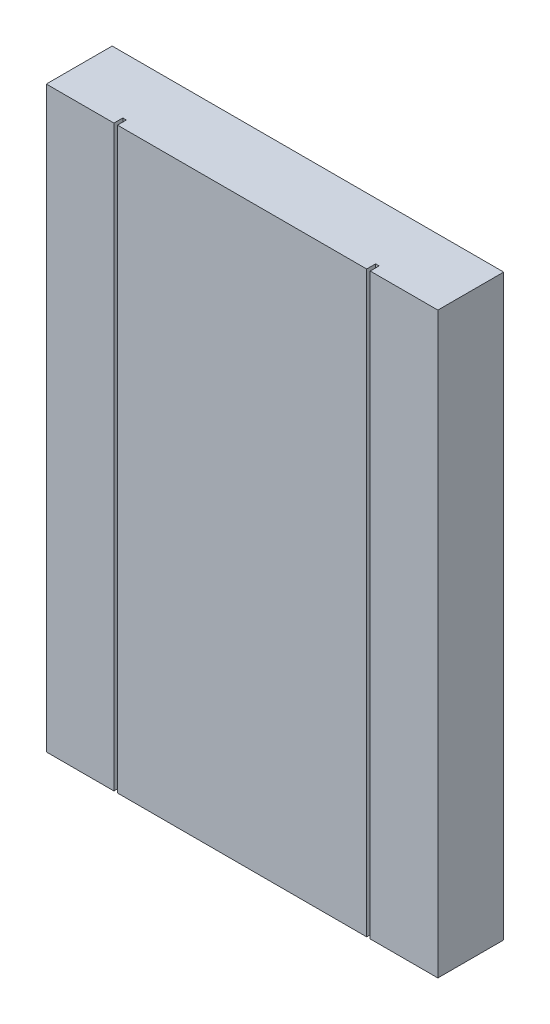
SolidWorks part; units mm, degrees
ref_plane "Front Plane" through (0, 0, 0) normal (0, 0, 1) x (1, 0, 0)
ref_plane "Top Plane" through (0, 0, 0) normal (0, 1, 0) x (1, 0, 0)
ref_plane "Right Plane" through (0, 0, 0) normal (1, 0, 0) x (0, 0, -1)
sketch "Sketch1" plane through (0, 0, 0) normal (0, 0, 1) x (1, 0, 0)
  line L1 (-27.94, -41.275) -> (27.94, -41.275)
  line L2 (-27.94, -41.275) -> (-27.94, 41.275)
  line L3 (-27.94, 41.275) -> (27.94, 41.275)
  line L4 (27.94, -41.275) -> (27.94, 41.275)
  line L5 (-27.94, -41.275) -> (27.94, 41.275) construction
  line L6 (-27.94, 41.275) -> (27.94, -41.275) construction
  point P0 (0, 0)
  dimension "D1" = 82.55
  dimension "D2" = 55.88
extrude "Boss-Extrude1" add sketch "Sketch1" along normal blind 9.398
sketch "Sketch2" plane through (0, 0, 9.398) normal (0, 0, 1) x (1, 0, 0)
  line L0 (-17.78, 41.275) -> (-17.78, -41.275)
  line L1 (27.94, 41.275) -> (-27.94, 41.275) construction
  line L2 (-27.94, -41.275) -> (27.94, -41.275) construction
  dimension "D1" = 17.78
extrude "Cut-Extrude-Thin1" cut sketch "Sketch2" against normal blind 1.27 and the other way through all thin
mirror "Mirror1" about plane through (0, 0, 0) normal (1, 0, 0) of "Cut-Extrude-Thin1"
